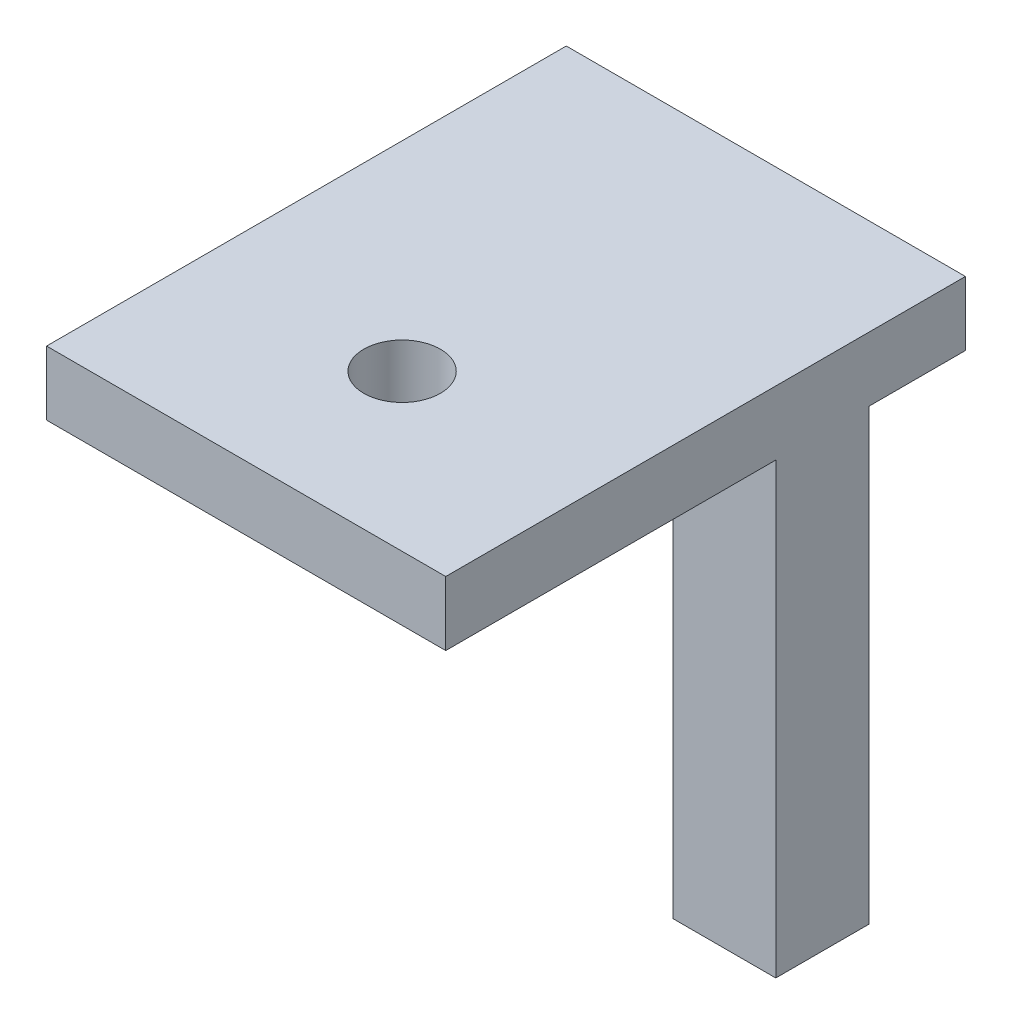
SolidWorks part; units mm, degrees
ref_plane "Front Plane" through (0, 0, 0) normal (0, 0, 1) x (1, 0, 0)
ref_plane "Top Plane" through (0, 0, 0) normal (0, 1, 0) x (1, 0, 0)
ref_plane "Right Plane" through (0, 0, 0) normal (1, 0, 0) x (0, 0, -1)
sketch "Sketch1" plane through (0, 0, 0) normal (0, 1, 0) x (1, 0, 0)
  line L1 (-31.1, 40.4921) -> (31.1, 40.4921)
  line L2 (-31.1, 40.4921) -> (-31.1, -40.4921)
  line L3 (-31.1, -40.4921) -> (31.1, -40.4921)
  line L4 (31.1, 40.4921) -> (31.1, -40.4921)
  line L5 (-31.1, 40.4921) -> (31.1, -40.4921) construction
  line L6 (-31.1, -40.4921) -> (31.1, 40.4921) construction
  point P0 (0, 0)
  dimension "D1" = 62.2
  dimension "D2" = 80.9841
extrude "Boss-Extrude1" add sketch "Sketch1" along normal blind 10
sketch "Sketch2" plane through (0, 10, 0) normal (0, 1, 0) x (1, 0, 0)
  line L0 (-31.1, -40.4921) -> (31.1, -40.4921) construction
  circle A0 centre (0, -16.1921) radius 5.969
  dimension "D1" = 24.3
extrude "Cut-Extrude1" cut sketch "Sketch2" against normal blind 10
sketch "Sketch3" plane through (0, 0, 0) normal (0, -1, 0) x (1, 0, 0)
  line L0 (31.1, -40.4921) -> (-31.1, -40.4921) construction
  line L1 (31.1, -25.4921) -> (15.1, -25.4921)
  line L2 (31.1, -25.4921) -> (31.1, -10.9394)
  line L3 (31.1, -10.9394) -> (15.1, -10.9394)
  line L4 (15.1, -25.4921) -> (15.1, -10.9394)
  dimension "D1" = 16
  dimension "D2" = 15
  dimension "D3" = 14.5526
extrude "Boss-Extrude2" add sketch "Sketch3" along normal blind 69.9
